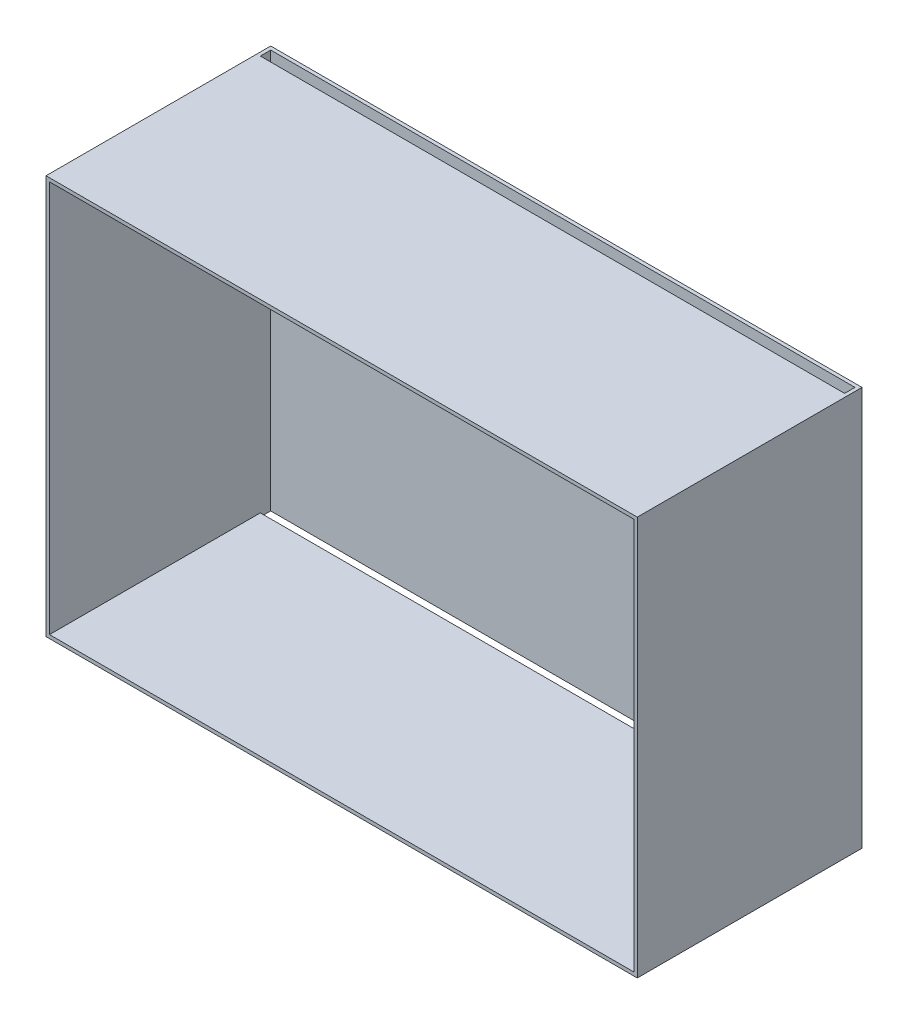
SolidWorks part; units mm, degrees
material "Custom Plastic"
ref_plane "X-Y Datum" through (0, 0, 0) normal (0, 0, 1) x (1, 0, 0)
ref_plane "X-Z Datum" through (0, 0, 0) normal (0, 1, 0) x (1, 0, 0)
ref_plane "Y-Z Datum" through (0, 0, 0) normal (1, 0, 0) x (0, 0, -1)
sketch "Sketch1" plane through (0, 0, 0) normal (0, 0, 1) x (1, 0, 0)
  line L0 (-267.335, 180.467) -> (-267.335, -180.467)
  line L1 (-264.16, 177.292) -> (264.16, 177.292)
  line L2 (-264.16, 177.292) -> (-264.16, -177.292)
  line L3 (-264.16, -177.292) -> (264.16, -177.292)
  line L4 (264.16, 177.292) -> (264.16, -177.292)
  line L5 (-264.16, 177.292) -> (264.16, -177.292) construction
  line L6 (-264.16, -177.292) -> (264.16, 177.292) construction
  line L7 (-267.335, -180.467) -> (267.335, -180.467)
  line L8 (267.335, 180.467) -> (267.335, -180.467)
  line L9 (-267.335, 180.467) -> (267.335, 180.467)
  point P0 (0, 0)
  dimension "D1" = 354.584
  dimension "D2" = 528.32
  dimension "D3" = 3.175
extrude "Boss-Extrude1" add sketch "Sketch1" along normal blind 203.2 contours L4 L1 L2 L3 | L9 L0 L7 L8 L1 L4 L3 L2
shell "Shell1" thickness 3.175
sketch "Sketch2" plane through (0, -180.467, 0) normal (0, -1, 0) x (1, 0, 0)
  line L1 (-267.335, 12.573) -> (267.335, 12.573)
  line L2 (-267.335, 3.175) -> (267.335, 3.175)
  line L3 (-267.335, 3.175) -> (267.335, 3.175)
  line L4 (-267.335, 203.2) -> (-267.335, 0) construction
  line L5 (267.335, 203.2) -> (267.335, 0) construction
  line L8 (-264.16, 203.2) -> (-264.16, 0)
  line L9 (-264.16, 203.2) -> (-264.16, 0)
  line L11 (264.16, 203.2) -> (264.16, 0)
  line L12 (264.16, 203.2) -> (264.16, 0)
  dimension "D2" = 9.398
  dimension "D1" = 3.175
  dimension "D3" = 3.175
  dimension "D4" = 3.175
extrude "Cut-Extrude1" cut sketch "Sketch2" against normal through all contours L12 L1 L9 L3
